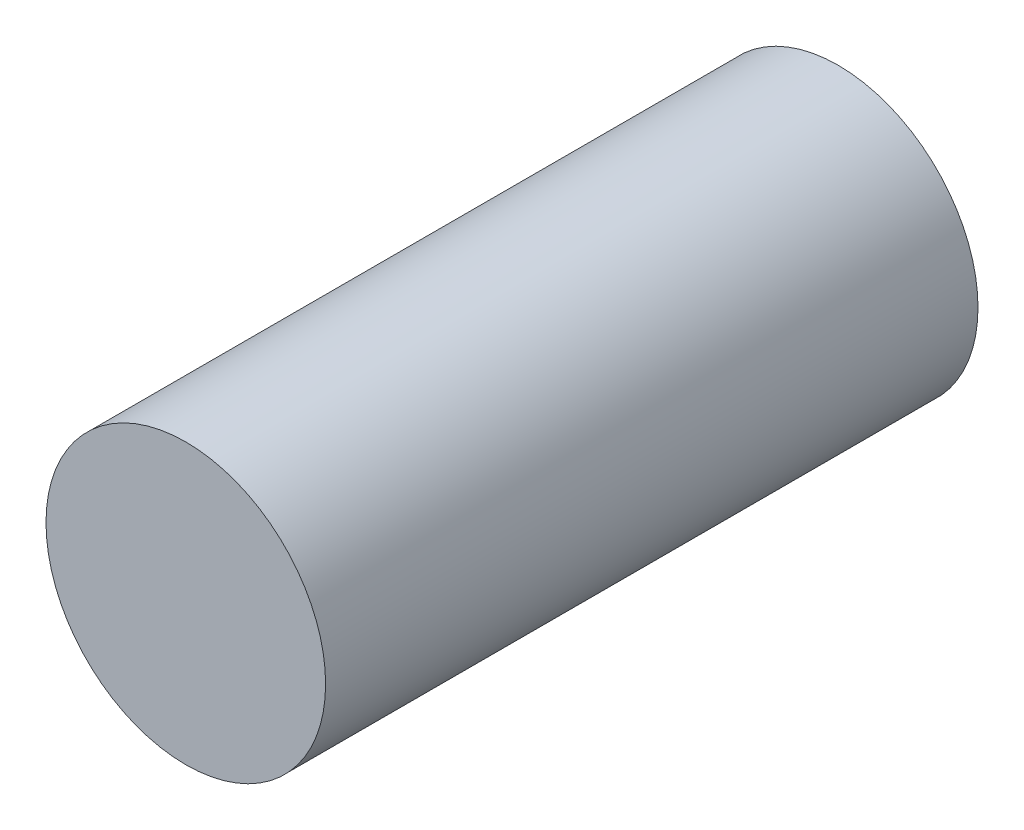
SolidWorks part; units mm, degrees
ref_plane "Alzado" through (0, 0, 0) normal (0, 0, 1) x (1, 0, 0)
ref_plane "Planta" through (0, 0, 0) normal (0, 1, 0) x (1, 0, 0)
ref_plane "Vista lateral" through (0, 0, 0) normal (1, 0, 0) x (0, 0, -1)
sketch "Croquis1" plane through (0, 0, 0) normal (0, 0, 1) x (1, 0, 0)
  circle A0 centre (0, 0) radius 3
  dimension "D1" = 6
extrude "Saliente-Extruir1" add sketch "Croquis1" along normal blind 14
